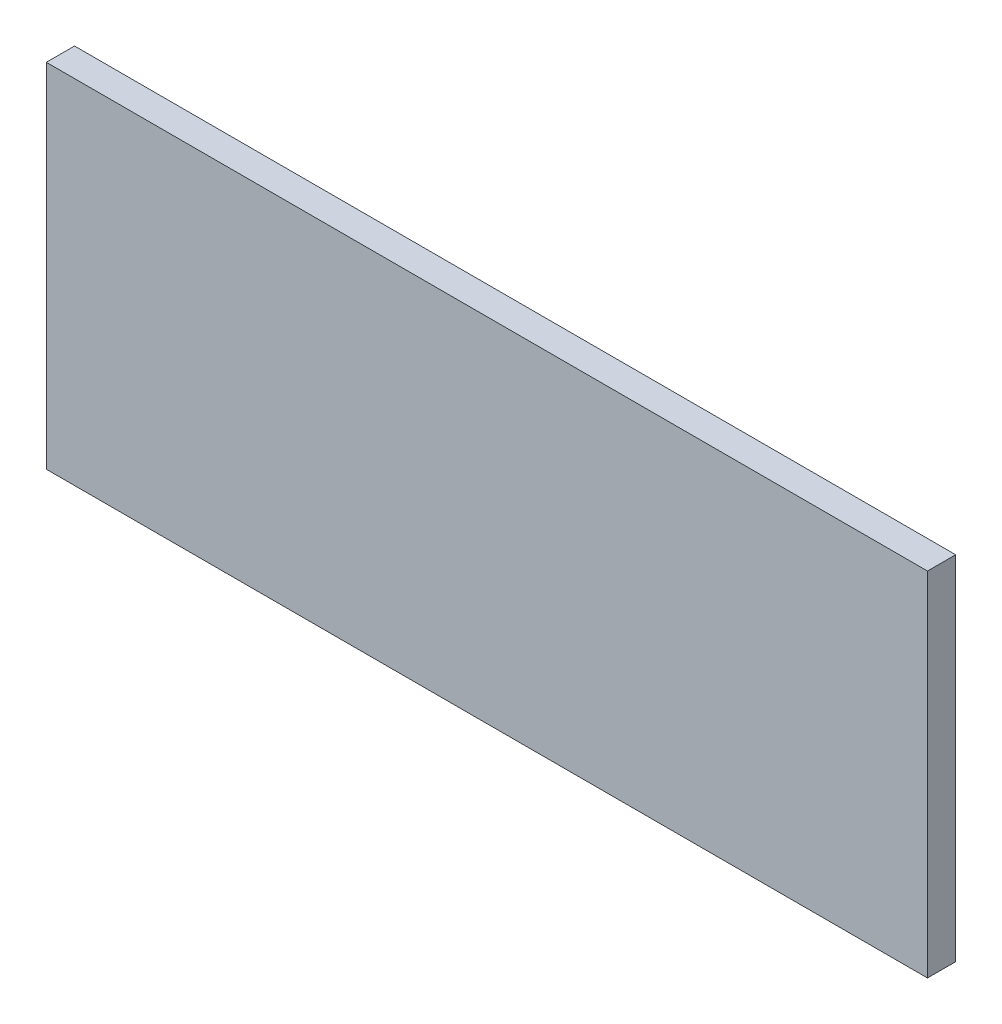
SolidWorks part; units mm, degrees
ref_plane "Front Plane" through (0, 0, 0) normal (0, 0, 1) x (1, 0, 0)
ref_plane "Top Plane" through (0, 0, 0) normal (0, 1, 0) x (1, 0, 0)
ref_plane "Right Plane" through (0, 0, 0) normal (1, 0, 0) x (0, 0, -1)
sketch "Sketch1" plane through (0, 0, 0) normal (0, 0, 1) x (1, 0, 0)
  line L1 (-125, 100) -> (125, 100)
  line L2 (-125, 100) -> (-125, 0)
  line L3 (-125, 0) -> (125, 0)
  line L4 (125, 100) -> (125, 0)
  line L5 (-125, 100) -> (125, 0) construction
  line L6 (-125, 0) -> (125, 100) construction
  point P0 (0, 50)
  dimension "D1" = 250
  dimension "D2" = 100
extrude "Boss-Extrude1" add sketch "Sketch1" along normal blind 8
